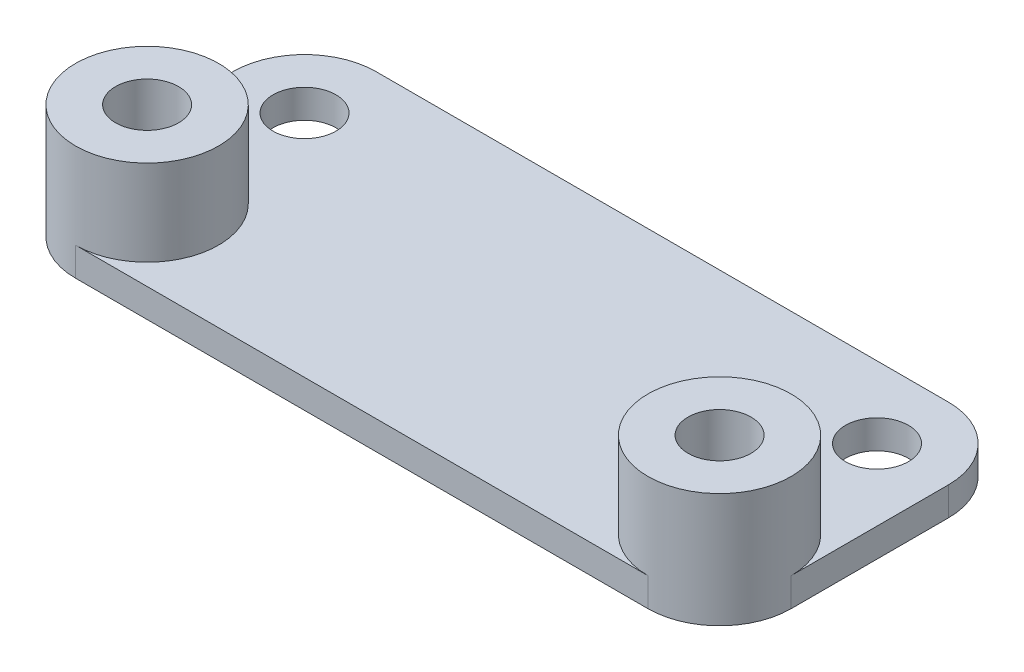
SolidWorks part; units mm, degrees
ref_plane "前视基准面" through (0, 0, 0) normal (0, 0, 1) x (1, 0, 0)
ref_plane "上视基准面" through (0, 0, 0) normal (0, 1, 0) x (1, 0, 0)
ref_plane "右视基准面" through (0, 0, 0) normal (1, 0, 0) x (0, 0, -1)
sketch "草图1" plane through (0, 0, 0) normal (0, 1, 0) x (1, 0, 0)
  line L0 (-20, 12.5) -> (20, 12.5)
  line L6 (25, 7.5) -> (25, -3.5)
  line L11 (20, -8.5) -> (-20, -8.5)
  line L16 (-25, -3.5) -> (-25, 7.5)
  circle A0 centre (20, 7.5) radius 2.2
  circle A1 centre (-20, 7.5) radius 2.2
  circle A8 centre (20, -3.5) radius 2.2
  circle A9 centre (-20, -3.5) radius 2.2
  arc A10 (-20, -8.5) -> (-25, -3.5) centre (-20, -3.5) cw
  arc A11 (25, -3.5) -> (20, -8.5) centre (20, -3.5) cw
  arc A12 (20, 12.5) -> (25, 7.5) centre (20, 7.5) cw
  arc A13 (-25, 7.5) -> (-20, 12.5) centre (-20, 7.5) cw
  point P0 (0, 0)
  point P10 (0, 0)
  dimension "D1" = 5
extrude "凸台-拉伸1" add sketch "草图1" along normal blind 2
sketch "草图2" plane through (0, 2, 0) normal (0, 1, 0) x (1, 0, 0)
  circle A0 centre (-20, -3.5) radius 5
  circle A1 centre (20, -3.5) radius 5
  circle A2 centre (-20, -3.5) radius 2.2
  circle A3 centre (20, -3.5) radius 2.2
extrude "凸台-拉伸3" add sketch "草图2" along normal blind 6
